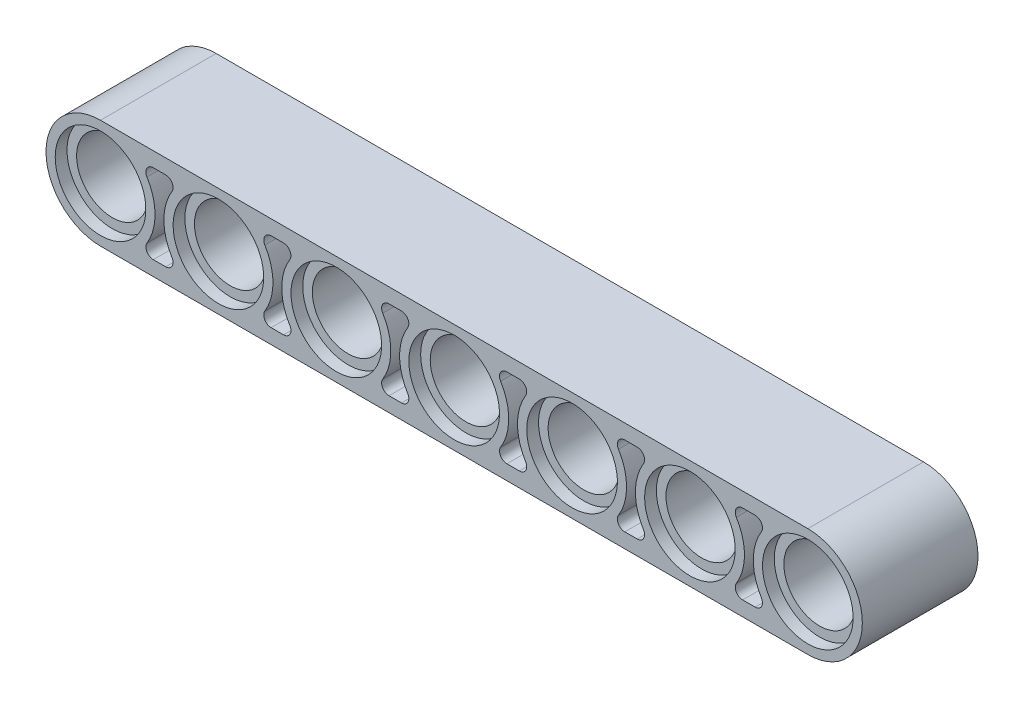
SolidWorks part; units mm, degrees
material "ABS"
ref_plane "Zero X (Front)" through (0, 0, 0) normal (0, 0, 1) x (1, 0, 0)
ref_plane "Zero Z (Top)" through (0, 0, 0) normal (0, 1, 0) x (1, 0, 0)
ref_plane "Zero Y(Right)" through (0, 0, 0) normal (1, 0, 0) x (0, 0, -1)
sketch "Sketch1" plane through (0, 0, 0) normal (0, 1, 0) x (1, 0, 0)
  line L0 (0, 2.425) -> (0, -2.425) construction
  line L1 (-3.7, 3.925) -> (-3.7, -3.925)
  line L2 (-3.7, -3.925) -> (-3.075, -3.925)
  line L3 (-3.075, -3.925) -> (-3.075, -3.125)
  line L4 (-3.075, -3.125) -> (-2.425, -3.125)
  line L5 (-2.425, -3.125) -> (-2.425, 3.125)
  line L6 (-2.425, 3.125) -> (-3.075, 3.125)
  line L7 (-3.075, 3.125) -> (-3.075, 3.925)
  line L8 (-3.075, 3.925) -> (-3.7, 3.925)
  line L9 (-1.7975, 0) -> (1.7975, 0) construction
  circle A0 centre (0, 0) radius 2.425 construction
  dimension "D1" = 4.85
  dimension "D2" = 7.85
  dimension "D3" = 7.4
  dimension "D4" = 6.25
  dimension "D5" = 6.15
revolve "Revolve1" add sketch "Sketch1" angle 360 about L0
sketch "Sketch2" plane through (0, 0, 3.925) normal (0, 0, 1) x (1, 0, 0)
  line L0 (0, 3.7) -> (-8, 3.7)
  line L1 (-1.7975, 0) -> (1.7975, 0) construction
  line L2 (-8, 3.7) -> (-8, 3.2)
  line L3 (0, -3.7) -> (-8, -3.7)
  line L4 (-3.5777, -2.7) -> (-4.4223, -2.7)
  line L5 (-3.5777, 2.7) -> (-4.4223, 2.7)
  line L6 (0, 0) -> (-8, 0) construction
  line L7 (-8, -3.2) -> (-8, -3.7)
  line L8 (0, 3.7) -> (0, 3.2)
  line L9 (0, -3.2) -> (0, -3.7)
  circle A0 centre (0, 0) radius 3.7 construction
  arc A1 (-3.1518, 1.9381) -> (-3.1518, -1.9381) centre (0, 0) ccw
  arc A2 (-4.8482, -1.9381) -> (-4.8482, 1.9381) centre (-8, 0) ccw
  arc A3 (-3.1518, -1.9381) -> (-3.5777, -2.7) centre (-3.5777, -2.2) cw
  arc A4 (-4.8482, 1.9381) -> (-4.4223, 2.7) centre (-4.4223, 2.2) cw
  arc A5 (-4.8482, -1.9381) -> (-4.4223, -2.7) centre (-4.4223, -2.2) ccw
  arc A6 (-3.5777, 2.7) -> (-3.1518, 1.9381) centre (-3.5777, 2.2) cw
  arc A7 (-8, -3.2) -> (-8, 3.2) centre (-8, 0) ccw
  arc A12 (0, 3.2) -> (0, -3.2) centre (0, 0) ccw
  dimension "D2" = 0.5
  dimension "D3" = 0.5
  dimension "D1" = 1
extrude "Boss-Extrude1" add sketch "Sketch2" against normal up to surface (7.85 mm away) up to face at (-3.7, 0, -3.925)
sketch "Sketch3" plane through (0, 0, 0) normal (0, 0, 1) x (1, 0, 0)
  line L0 (-3.5777, 2.7) -> (-4.4223, 2.7) construction
  line L1 (-3.5777, -2.7) -> (-4.4223, -2.7) construction
  line L2 (-3.5777, 2.7) -> (-4.4223, 2.7)
  line L3 (-3.5777, -2.7) -> (-4.4223, -2.7)
  arc A0 (-4.8482, -1.9381) -> (-4.8482, 1.9381) centre (-8, 0) ccw construction
  arc A1 (-4.4223, 2.7) -> (-4.8482, 1.9381) centre (-4.4223, 2.2) ccw construction
  arc A2 (-3.1518, 1.9381) -> (-3.5777, 2.7) centre (-3.5777, 2.2) ccw construction
  arc A3 (-3.5777, -2.7) -> (-3.1518, -1.9381) centre (-3.5777, -2.2) ccw construction
  arc A4 (-4.8482, -1.9381) -> (-4.4223, -2.7) centre (-4.4223, -2.2) ccw construction
  arc A6 (-4.8482, -1.9381) -> (-4.8482, 1.9381) centre (-8, 0) ccw
  arc A7 (-4.4223, 2.7) -> (-4.8482, 1.9381) centre (-4.4223, 2.2) ccw
  arc A8 (-3.1518, 1.9381) -> (-3.5777, 2.7) centre (-3.5777, 2.2) ccw
  arc A9 (-3.5777, -2.7) -> (-3.1518, -1.9381) centre (-3.5777, -2.2) ccw
  arc A10 (-4.8482, -1.9381) -> (-4.4223, -2.7) centre (-4.4223, -2.2) ccw
  arc A11 (-3.1518, 1.9381) -> (-3.1518, -1.9381) centre (0, 0) ccw construction
  arc A12 (-3.1518, 1.9381) -> (-3.1518, -1.9381) centre (0, 0) ccw
extrude "Boss-Extrude2" add sketch "Sketch3" along normal mid plane 1.2
pattern_linear "LPattern1" count 7 spacing 8 along (1, 0, 0) of "Revolve1", "Boss-Extrude1", "Boss-Extrude2"
sketch "Sketch4" plane through (0, 0, 3.925) normal (0, 0, 1) x (1, 0, 0)
  line L0 (48, 3.7) -> (-8, 3.7) construction
  line L1 (-8, -3.7) -> (48, -3.7) construction
  line L2 (0, 3.7) -> (-8, 3.7)
  line L3 (-8, -3.7) -> (0, -3.7)
  line L4 (-8, -3.2) -> (-8, -3.7) construction
  line L5 (-8, 3.7) -> (-8, -3.7)
  arc A0 (-3.1518, 1.9381) -> (-3.1518, -1.9381) centre (0, 0) ccw construction
  arc A1 (0, 3.7) -> (0, -3.7) centre (0, 0) ccw
extrude "Cut-Extrude1" cut sketch "Sketch4" against normal through all
